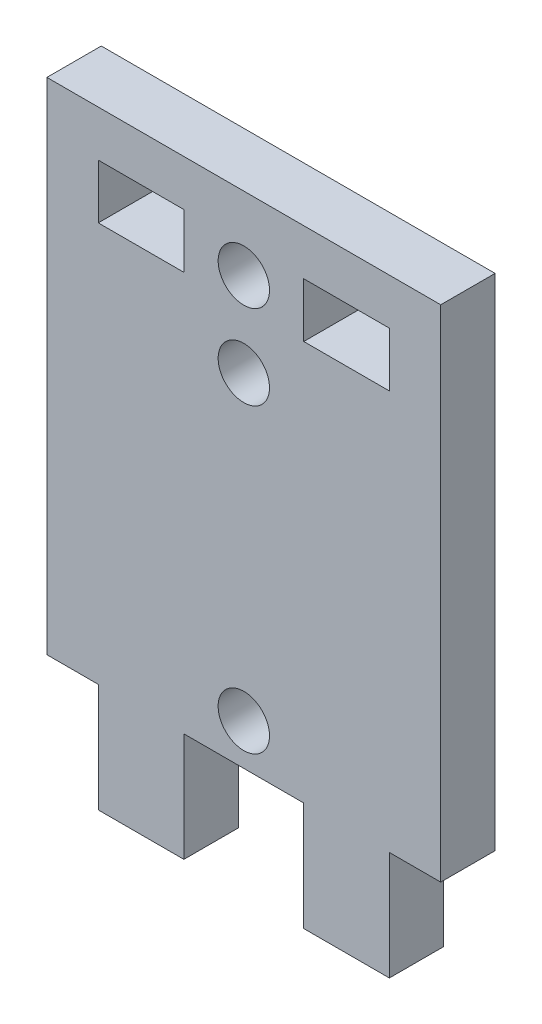
SolidWorks part; units mm, degrees
ref_plane "前视基准面" through (0, 0, 0) normal (0, 0, 1) x (1, 0, 0)
ref_plane "上视基准面" through (0, 0, 0) normal (0, 1, 0) x (1, 0, 0)
ref_plane "右视基准面" through (0, 0, 0) normal (1, 0, 0) x (0, 0, -1)
sketch "Sketch1" plane through (0, 0, 0) normal (0, 0, 1) x (1, 0, 0)
  line L0 (-34.4573, 0) -> (37.4903, 0) construction
  line L1 (0, 37.661) -> (0, -47.6728) construction
  line L2 (-11.5, 0) -> (-11.5, -11.2)
  line L3 (-11.5, -11.2) -> (-8.5, -11.2)
  line L4 (-8.5, -11.2) -> (-8.5, -17.55)
  line L5 (-8.5, -17.55) -> (-3.5, -17.55)
  line L6 (-3.5, -17.55) -> (-3.5, -11.2)
  line L7 (-3.5, -11.2) -> (3.5, -11.2)
  line L8 (3.5, -17.55) -> (3.5, -11.2)
  line L9 (8.5, -17.55) -> (3.5, -17.55)
  line L10 (8.5, -11.2) -> (8.5, -17.55)
  line L11 (11.5, -11.2) -> (8.5, -11.2)
  line L12 (11.5, 0) -> (11.5, -11.2)
  line L13 (-6, -17.55) -> (-6, -26.3905) construction
  line L14 (6, -17.55) -> (6, -25.1219) construction
  line L15 (-11.5, 0) -> (-11.5, 18)
  line L16 (-11.5, 18) -> (11.5, 18)
  line L17 (11.5, 18) -> (11.5, 0)
  point P13 (0, -11.2)
  dimension "D4" = 11.2
  dimension "D5" = 23
  dimension "D1" = 5
  dimension "D2" = 6.35
  dimension "D3" = 12
  dimension "D6" = 18
extrude "Boss-Extrude1" add sketch "Sketch1" along normal blind 3.175
sketch "Sketch2" plane through (0, 0, 3.175) normal (0, 0, 1) x (1, 0, 0)
  line L0 (-14.6942, 0) -> (18.7254, 0) construction
  line L1 (0, 11.9888) -> (0, -6.1297) construction
  circle A0 centre (0, -8.8) radius 1.5
  circle A1 centre (0, 8.8) radius 1.5
  dimension "D1" = 3
  dimension "D2" = 17.6
extrude "Cut-Extrude1" cut sketch "Sketch2" against normal through all
sketch "Sketch3" plane through (0, 0, 3.175) normal (0, 0, 1) x (1, 0, 0)
  line L0 (0, 13.7442) -> (0, -0.2709) construction
  line L1 (-3.2174, 13.7291) -> (8.7989, 13.7291) construction
  line L2 (-3.5, 15.3166) -> (-8.5, 12.1416) construction
  line L3 (3.5, 12.1416) -> (8.5, 12.1416)
  line L4 (3.5, 12.1416) -> (3.5, 15.3166)
  line L5 (3.5, 15.3166) -> (8.5, 15.3166)
  line L6 (8.5, 12.1416) -> (8.5, 15.3166)
  line L7 (3.5, 12.1416) -> (8.5, 15.3166) construction
  line L8 (3.5, 15.3166) -> (8.5, 12.1416) construction
  line L9 (-3.5, 12.1416) -> (-8.5, 15.3166) construction
  line L10 (-8.5, 12.1416) -> (-8.5, 15.3166)
  line L11 (-3.5, 15.3166) -> (-8.5, 15.3166)
  line L12 (-3.5, 12.1416) -> (-3.5, 15.3166)
  line L13 (-3.5, 12.1416) -> (-8.5, 12.1416)
  circle A0 centre (0, 13.7291) radius 1.5
  point P7 (6, 13.7291)
  point P16 (-6, 13.7291)
  dimension "D2" = 3
  dimension "D1" = 14
  dimension "D3" = 3.175
  dimension "D4" = 5
  dimension "D5" = 12
extrude "Cut-Extrude2" cut sketch "Sketch3" against normal through all
